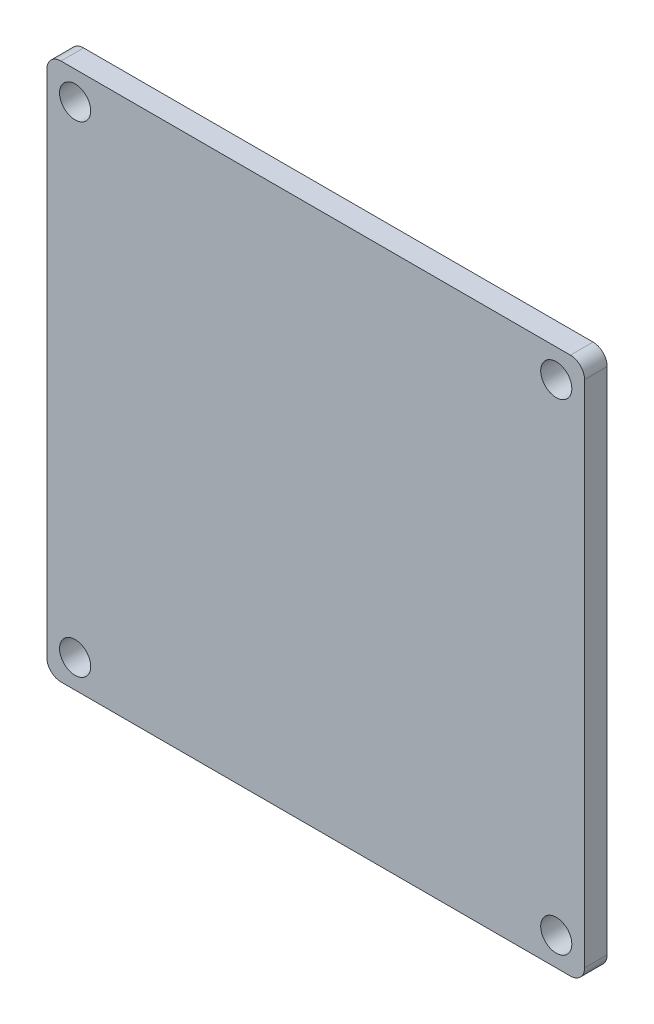
SolidWorks part; units mm, degrees
ref_plane "정면" through (0, 0, 0) normal (0, 0, 1) x (1, 0, 0)
ref_plane "윗면" through (0, 0, 0) normal (0, 1, 0) x (1, 0, 0)
ref_plane "우측면" through (0, 0, 0) normal (1, 0, 0) x (0, 0, -1)
sketch "스케치1" plane through (0, 0, 0) normal (0, 0, 1) x (1, 0, 0)
  line L0 (19, 19) -> (-19, -19) construction
  line L1 (-19, 19) -> (19, 19)
  line L2 (-19, 19) -> (-19, -19)
  line L3 (-19, -19) -> (19, -19)
  line L4 (19, 19) -> (19, -19)
  dimension "D1" = 38
  dimension "D2" = 38
extrude "보스-돌출1" add sketch "스케치1" along normal blind 1.6
sketch "스케치2" plane through (0, 0, 1.6) normal (0, 0, 1) x (1, 0, 0)
  line L0 (-17, 17) -> (17, 17) construction
  line L1 (17, 17) -> (17, -17) construction
  line L2 (17, -17) -> (-17, -17) construction
  line L3 (-17, -17) -> (-17, 17) construction
  line L4 (17, 17) -> (-17, -17) construction
  circle A0 centre (-17, 17) radius 1.1
  circle A1 centre (17, -17) radius 1.1
  circle A2 centre (17, 17) radius 1.1
  circle A3 centre (-17, -17) radius 1.1
  point P2 (17.0614, 17.3392)
  point P4 (-15.7882, 15.7882)
  point P6 (17.0614, -15.5335)
  point P8 (17.0614, 17.0614)
  point P12 (-17.0614, -16.7836)
  dimension "D1" = 2.2
  dimension "D2" = 34
extrude "컷-돌출1" cut sketch "스케치2" against normal through all
fillet "필렛1" radius 1 4 edges at (-19, -19, 0.8) (19, -19, 0.8) (19, 19, 0.8) (-19, 19, 0.8)
